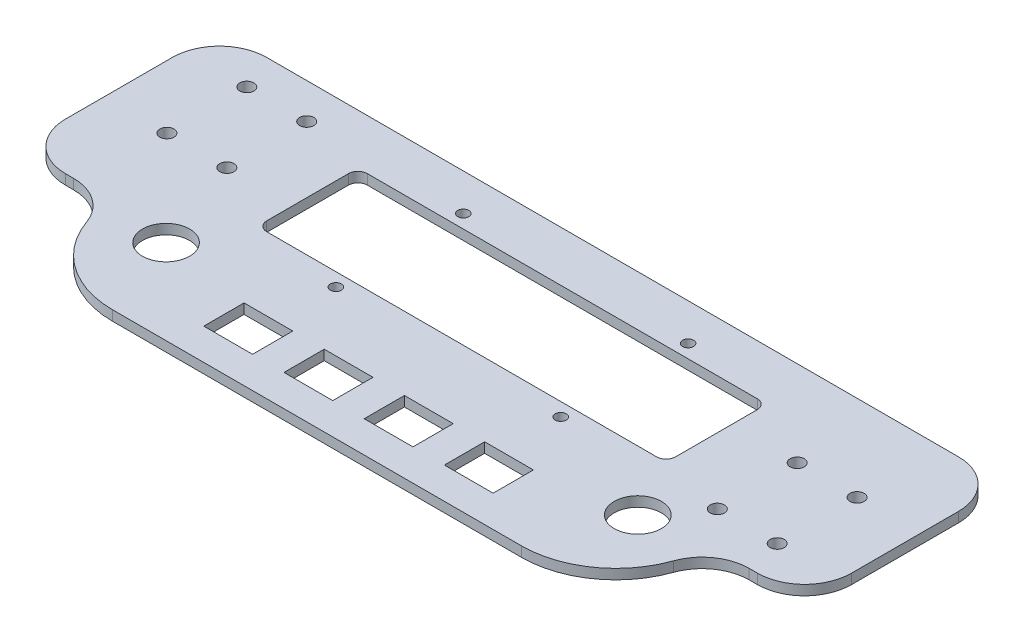
SolidWorks part; units mm, degrees
ref_plane "Front Plane" through (0, 0, 0) normal (0, 0, 1) x (1, 0, 0)
ref_plane "Top Plane" through (0, 0, 0) normal (0, 1, 0) x (1, 0, 0)
ref_plane "Right Plane" through (0, 0, 0) normal (1, 0, 0) x (0, 0, -1)
sketch "Sketch3" plane through (0, 0, 0) normal (0, 1, 0) x (1, 0, 0)
  line L0 (-125, 0) -> (0, 0) construction
  line L5 (65, 0) -> (0, 0) construction
  line L6 (0, 32) -> (0, 0) construction
  line L7 (-125, -32) -> (125, -32)
  line L8 (-125, -32) -> (-125, 32)
  line L9 (-125, 32) -> (125, 32)
  line L10 (125, -32) -> (125, 32)
  line L11 (-65, 16) -> (65, 16)
  line L12 (-65, 16) -> (-65, -16)
  line L13 (-105.025, 20.7) -> (-85.975, 20.7)
  line L14 (-105.025, 20.7) -> (-105.025, -4.7)
  line L15 (-105.025, -4.7) -> (-85.975, -4.7)
  line L16 (-85.975, 20.7) -> (-85.975, -4.7)
  line L17 (-65, -16) -> (65, -16)
  line L18 (85.975, 4.7) -> (105.025, 4.7)
  line L19 (85.975, 4.7) -> (85.975, -20.7)
  line L20 (85.975, -20.7) -> (105.025, -20.7)
  line L21 (105.025, 4.7) -> (105.025, -20.7)
  line L22 (65, 16) -> (65, -16)
  line L23 (0, -16) -> (0, -32) construction
  line L24 (-35.75, 20.25) -> (-35.75, -20.25) construction
  line L25 (-35.75, 20.25) -> (35.75, 20.25) construction
  line L26 (-35.75, -20.25) -> (35.75, -20.25) construction
  line L27 (35.75, -20.25) -> (35.75, 20.25) construction
  line L28 (-65, -32) -> (65, -32) construction
  line L31 (-65, -2) -> (65, -2)
  line L34 (-65, -62) -> (65, -62)
  line L35 (0, -32) -> (0, 0) construction
  circle A5 centre (-35.75, 20.25) radius 1.75
  circle A6 centre (-35.75, -20.25) radius 1.75
  circle A7 centre (35.75, 20.25) radius 1.75
  circle A8 centre (35.75, -20.25) radius 1.75
  arc A13 (-65, -2) -> (-65, -62) centre (-65, -32) ccw
  arc A14 (65, -62) -> (65, -2) centre (65, -32) ccw
  point P13 (-105.025, 8)
  point P19 (-95.5, 20.7)
  point P26 (85.975, -8)
  point P27 (95.5, 4.7)
  point P33 (0, 20.25)
  point P36 (-35.75, 0)
  point P39 (0, -32)
  point P45 (-95, -32)
  dimension "D14" = 40.5
  dimension "D16" = 3.5
  dimension "D18" = 30
  dimension "D2" = 95.5
  dimension "D3" = 250
  dimension "D4" = 64
  dimension "D5" = 19.05
  dimension "D6" = 25.4
  dimension "D7" = 95.5
  dimension "D8" = 130
  dimension "D9" = 19.05
  dimension "D10" = 25.4
  dimension "D11" = 32
  dimension "D12" = 40
  dimension "D13" = 40
  dimension "D15" = 71.5
  dimension "D17" = 130
extrude "Boss-Extrude1" add sketch "Sketch3" along normal blind 3.175
hole_wizard "M4 Clearance Hole1" positions "Sketch4" profile "Sketch5" hole size "M4" standard "ANSI Metric" end condition through all
sketch "Sketch4" plane through (0, 3.175, 0) normal (0, 1, 0) x (1, 0, 0)
  point P0 (-105.025, 20.7)
  point P3 (-85.975, 20.7)
  point P6 (-105.025, -4.7)
  point P9 (-85.975, -4.7)
  point P12 (85.975, 4.7)
  point P15 (105.025, 4.7)
  point P18 (105.025, -20.7)
  point P21 (85.975, -20.7)
  point P37 (0, 0)
  point P38 (0, 0)
  point P39 (0, 0)
  point P40 (0, 0)
sketch "Sketch5" plane through (-105.025, 3.175, -20.7) normal (1, 0, 0) x (0, 0, 1)
  line L0 (0, 0) -> (0, 3.175)
  line L1 (0, 3.175) -> (2.25, 3.175)
  line L2 (2.25, 3.175) -> (2.25, 0)
  line L5 (2.25, 0) -> (0, 0)
  line L11 (0, -6.35) -> (0, 107.95) construction
  dimension "Thru Hole Dia." = 4.5
  dimension "Thru Hole Depth" = 3.175
fillet "Fillet1" radius 15 6 edges at (125, 1.5875, 32) (125, 1.5875, -32) (-125, 1.5875, -32) (-125, 1.5875, 32) (95, 1.5875, 32) (-95, 1.5875, 32)
sketch "Sketch6" plane through (0, 3.175, 0) normal (0, 1, 0) x (1, 0, 0)
  line L0 (0, 0) -> (0, -62) construction
  line L1 (-46, -39.2) -> (-30.5, -39.2)
  line L2 (-46, -39.2) -> (-46, -52)
  line L3 (-46, -52) -> (-30.5, -52)
  line L4 (-30.5, -39.2) -> (-30.5, -52)
  line L5 (-20.5, -39.2) -> (-5, -39.2)
  line L6 (-20.5, -39.2) -> (-20.5, -52)
  line L7 (-20.5, -52) -> (-5, -52)
  line L8 (-5, -39.2) -> (-5, -52)
  line L9 (-65, -62) -> (65, -62) construction
  dimension "D1" = 15.5
  dimension "D2" = 12.8
  dimension "D3" = 10
  dimension "D4" = 5
  dimension "D5" = 10
extrude "Cut-Extrude1" cut sketch "Sketch6" against normal through all
sketch "Sketch7" plane through (0, 3.175, 0) normal (0, 1, 0) x (1, 0, 0)
  circle A0 centre (-75, -35) radius 7.5
  dimension "D1" = 15
  dimension "D2" = 75
  dimension "D3" = 35
extrude "Cut-Extrude2" cut sketch "Sketch7" against normal through all
mirror "Mirror1" about plane through (0, 0, 0) normal (1, 0, 0) of "Cut-Extrude2", "Cut-Extrude1"
fillet "Fillet2" radius 3 4 edges at (65, 1.5875, 16) (65, 1.5875, -16) (-65, 1.5875, -16) (-65, 1.5875, 16)
